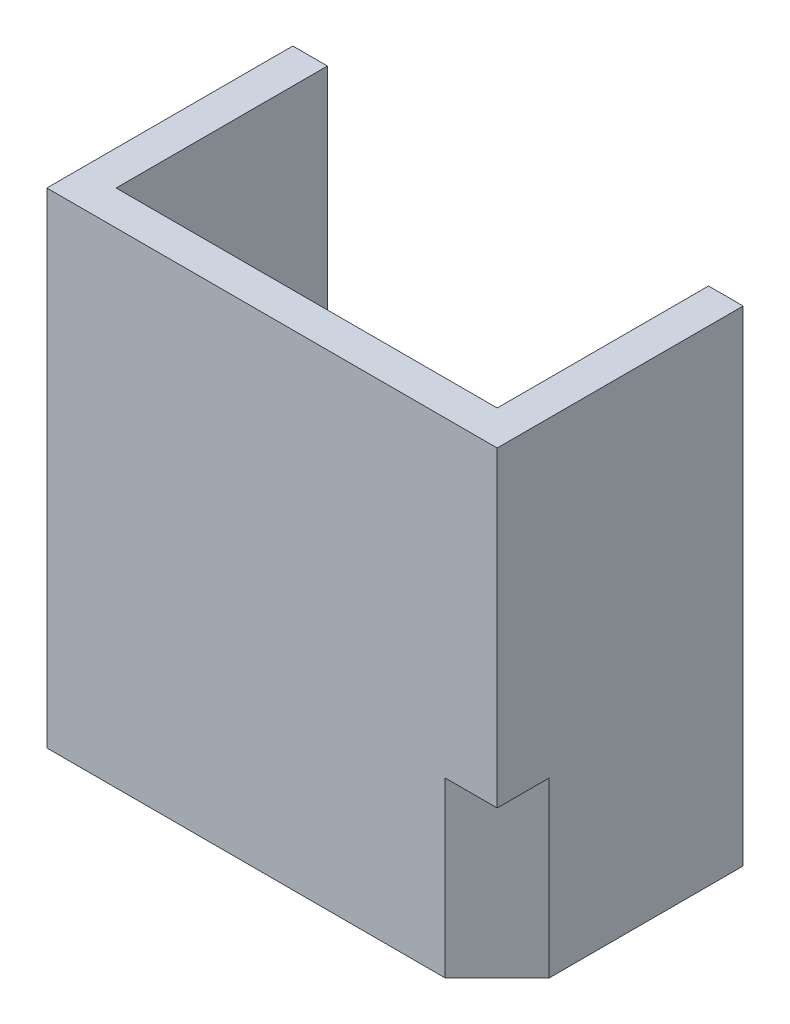
SolidWorks part; units mm, degrees
ref_plane "Front Plane" through (0, 0, 0) normal (0, 0, 1) x (1, 0, 0)
ref_plane "Top Plane" through (0, 0, 0) normal (0, 1, 0) x (1, 0, 0)
ref_plane "Right Plane" through (0, 0, 0) normal (1, 0, 0) x (0, 0, -1)
sketch "Sketch1" plane through (0, 0, 0) normal (0, 1, 0) x (1, 0, 0)
  line L1 (0, 0) -> (130, 0)
  line L2 (0, 0) -> (0, 90)
  line L3 (0, 90) -> (130, 90)
  line L4 (130, 0) -> (130, 90)
  dimension "D1" = 130
  dimension "D2" = 90
extrude "Boss-Extrude1" add sketch "Sketch1" along normal blind 140
sketch "Sketch3" plane through (0, 140, 0) normal (0, 1, 0) x (1, 0, 0)
  line L8 (10, 80) -> (10, 10)
  line L9 (10, 10) -> (120, 10)
  line L10 (120, 10) -> (120, 80)
  line L11 (120, 80) -> (10, 80)
  line L12 (10, 80) -> (10, 10)
  line L13 (10, 10) -> (120, 10)
  line L14 (120, 10) -> (120, 80)
  line L15 (120, 80) -> (10, 80)
  dimension "D1" = 10
extrude "Cut-Extrude1" cut sketch "Sketch3" against normal through all
sketch "Sketch4" plane through (0, 0, 0) normal (0, -1, 0) x (1, 0, 0)
  line L4 (120, -10) -> (120, -80) construction
  line L5 (120, -80) -> (10, -80) construction
  line L6 (10, -10) -> (120, -10) construction
  line L7 (120, -10) -> (120, -80)
  line L8 (19, -19) -> (19, -71)
  line L9 (19, -71) -> (111, -71)
  line L10 (111, -71) -> (111, -19)
  line L11 (111, -19) -> (19, -19)
  line L12 (19, -19) -> (19, -71)
  line L13 (19, -71) -> (111, -71)
  line L14 (111, -71) -> (111, -19)
  line L15 (111, -19) -> (19, -19)
  line L16 (120, -80) -> (10, -80)
  line L17 (10, -10) -> (120, -10)
  line M5 (120, -80) -> (10, -80)
  line M6 (10, -80) -> (10, -10)
  line M7 (10, -10) -> (120, -10)
  line M8 (120, -10) -> (120, -80)
  dimension "D1" = 19
extrude "Boss-Extrude2" add sketch "Sketch4" against normal blind 75 contours L15 L14 L13 L12 M5 M8 M7 M6
sketch "Sketch5" plane through (0, 0, 0) normal (0, -1, 0) x (1, 0, 0)
  line L4 (10, -80) -> (120, -80)
  line L5 (10, -10) -> (10, -80)
  line L6 (120, -10) -> (10, -10)
  line L7 (120, -80) -> (120, -10)
  line L8 (10, -80) -> (120, -80)
  line L9 (10, -10) -> (10, -80)
  line L10 (120, -10) -> (10, -10)
  line L11 (120, -80) -> (120, -10)
  line M9 (19, -19) -> (111, -19)
  line M10 (111, -19) -> (111, -71)
  line M11 (111, -71) -> (19, -71)
  line M12 (19, -71) -> (19, -19)
  dimension "D1" = 0
extrude "Cut-Extrude2" cut sketch "Sketch5" against normal offset from surface (65 mm away) 10 contours L8 L11 L10 L9 M12 M9 M10 M11 up to face at (65, 75, -45)
sketch "Sketch6" plane through (0, 0, -90) normal (0, 0, -1) x (-1, 0, 0)
  line L1 (-130, 140) -> (0, 140)
  line L2 (-130, 140) -> (-130, 0)
  line L3 (-130, 0) -> (0, 0)
  line L4 (0, 140) -> (0, 0)
extrude "Cut-Extrude3" cut sketch "Sketch6" against normal up to surface (19 mm away) up to face at (65, 70, -71)
sketch "Sketch7" plane through (0, 0, -19) normal (0, 0, -1) x (-1, 0, 0)
  line L0 (-111, 75) -> (-111, 65) construction
  line L1 (-111, 75) -> (-19, 75)
  line L2 (-111, 75) -> (-111, 65)
  line L3 (-111, 65) -> (-19, 65)
  line L4 (-19, 75) -> (-19, 65)
  line L5 (-111, 75) -> (-111, 65) construction
  line L6 (-111, 65) -> (-19, 65) construction
  line L7 (-19, 75) -> (-19, 65) construction
extrude "Cut-Extrude4" cut sketch "Sketch7" against normal up to surface (9 mm away) up to face at (65, 32.5, -10)
sketch "Sketch8" plane through (0, 0, 0) normal (0, 1, 0) x (1, 0, 0)
  line L5 (130, 0) -> (130, 15)
  line L6 (130, 0) -> (130, 71) construction
  line L7 (130, 15) -> (115, 0)
  line L8 (0, 0) -> (130, 0) construction
  line L9 (115, 0) -> (130, 0)
  dimension "D1" = 15
extrude "Cut-Extrude5" cut sketch "Sketch8" along normal blind 50
equation "\"PowerBracketThickness\"= 10"
equation "\"D1@Sketch3\"=\"PowerBracketThickness\""
equation "\"D1@Cut-Extrude2\"=\"PowerBracketThickness\""
